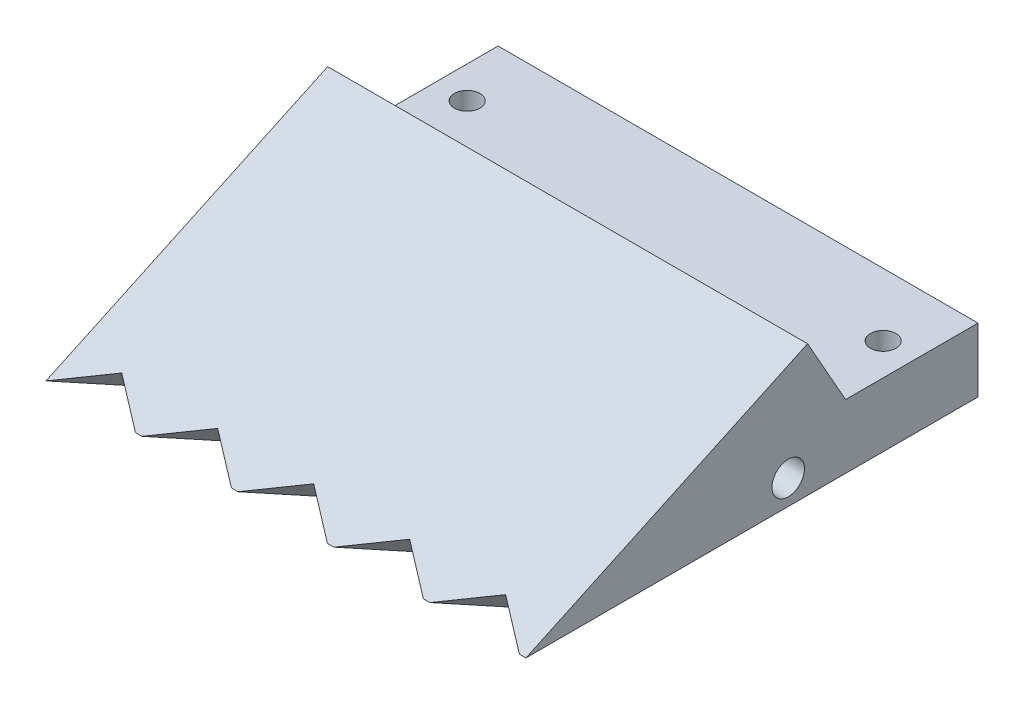
SolidWorks part; units mm, degrees
ref_plane "Front Plane" through (0, 0, 0) normal (0, 0, 1) x (1, 0, 0)
ref_plane "Top Plane" through (0, 0, 0) normal (0, 1, 0) x (1, 0, 0)
ref_plane "Right Plane" through (0, 0, 0) normal (1, 0, 0) x (0, 0, -1)
sketch "Sketch1" plane through (0, 0, 0) normal (1, 0, 0) x (0, 0, -1)
  line L0 (-35.4476, 4.1732) -> (35.2065, 4.1732)
  line L1 (35.2065, 4.1732) -> (35.2065, 14.1732)
  line L2 (35.2065, 14.1732) -> (14.5119, 14.1732)
  line L3 (14.5119, 14.1732) -> (8.5711, 24.6994)
  line L4 (8.5711, 24.6994) -> (-35.4476, 4.1732)
  dimension "D1" = 25
  dimension "D2" = 10
  dimension "D3" = 49.9595
extrude "Boss-Extrude1" add sketch "Sketch1" along normal blind 75
sketch "Sketch2" plane through (0, 14.1732, 0) normal (0, 1, 0) x (1, 0, 0)
  line L0 (0, -11.2894) -> (0, 11.2894) construction
  circle A0 centre (5, 25.3746) radius 2
  circle A1 centre (70, 25.3862) radius 2
  dimension "D1" = 4
  dimension "D2" = 4
  dimension "D3" = 65
  dimension "D4" = 5
extrude "Cut-Extrude1" cut sketch "Sketch2" against normal blind 10
sketch "Sketch3" plane through (0, 0, 0) normal (-1, 0, 0) x (0, 0, 1)
  circle A0 centre (-5.5476, 8.0335) radius 2.543
sketch "Sketch4" plane through (0, 17.0051, 7.9296) normal (0, 0.9063, 0.4226) x (1, 0, 0)
  line L0 (0, -30.3628) -> (7.0659, -25.1031)
  line L1 (0, -11.2894) -> (0, 11.2894) construction
  line L2 (75, -30.3628) -> (0, -30.3628) construction
  line L3 (7.0659, -25.1031) -> (13.9766, -30.3628)
  line L4 (22.0659, -25.1031) -> (28.9766, -30.3628)
  line L5 (15, -30.3628) -> (22.0659, -25.1031)
  line L6 (37.0659, -25.1031) -> (43.9766, -30.3628)
  line L7 (30, -30.3628) -> (37.0659, -25.1031)
  line L8 (52.0659, -25.1031) -> (58.9766, -30.3628)
  line L9 (45, -30.3628) -> (52.0659, -25.1031)
  line L10 (67.0659, -25.1031) -> (73.9766, -30.3628)
  line L11 (60, -30.3628) -> (67.0659, -25.1031)
  line L12 (13.9766, -30.3628) -> (0, -30.3628)
  line L13 (15, -30.3628) -> (28.9766, -30.3628)
  line L14 (43.9766, -30.3628) -> (30, -30.3628)
  line L15 (45, -30.3628) -> (58.9766, -30.3628)
  line L16 (73.9766, -30.3628) -> (60, -30.3628)
  dimension "D1" = 5
extrude "Cut-Extrude2" cut sketch "Sketch4" against normal blind 10
extrude "Cut-Extrude3" cut sketch "Sketch3" against normal blind 100 contours A0
chamfer "Chamfer1" distance 2 angle 45 2 edges at (70, 4.1732, -23.3862) (5, 4.1732, -23.3746)
